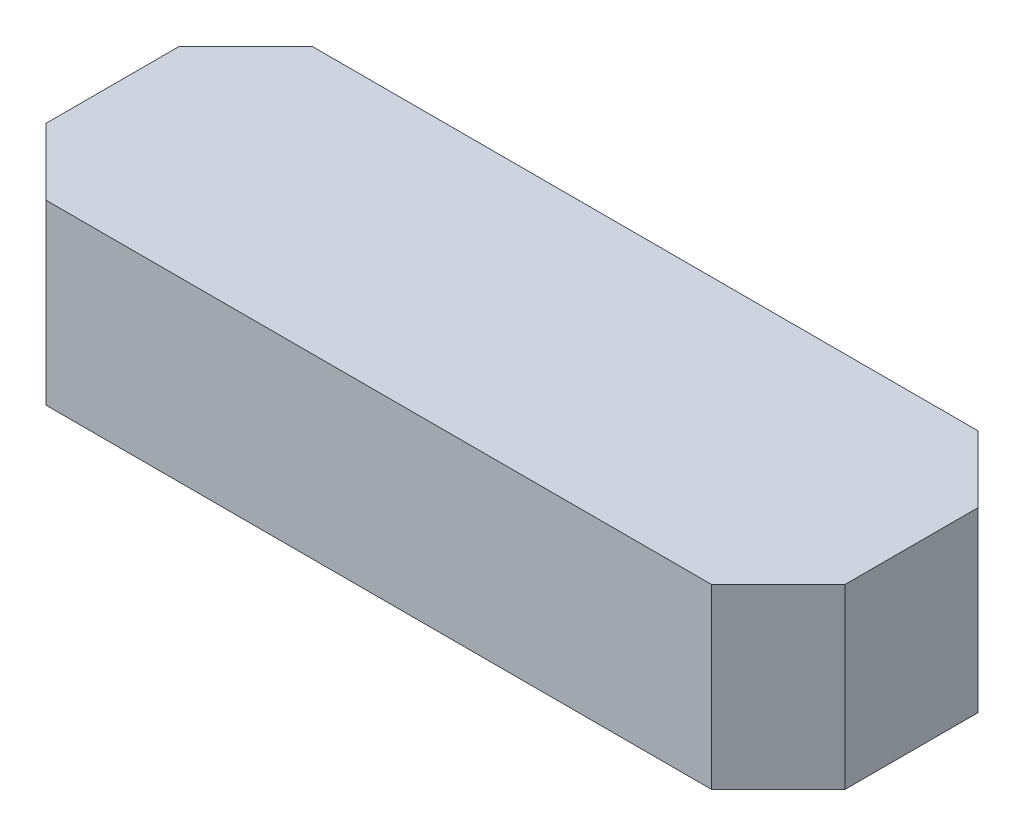
SolidWorks part; units mm, degrees
ref_plane "Front Plane" through (0, 0, 0) normal (0, 0, 1) x (1, 0, 0)
ref_plane "Top Plane" through (0, 0, 0) normal (0, 1, 0) x (1, 0, 0)
ref_plane "Right Plane" through (0, 0, 0) normal (1, 0, 0) x (0, 0, -1)
sketch "Sketch1" plane through (0, 0, 0) normal (0, 1, 0) x (1, 0, 0)
  line L4 (24.7236, 6.1432) -> (24.7236, 6.897)
  line L7 (-18, 6) -> (18, 6)
  line L8 (-18, 6) -> (-18, -6)
  line L9 (-18, -6) -> (18, -6)
  line L10 (18, 6) -> (18, -6)
  line L11 (-18, 6) -> (18, -6) construction
  line L12 (-18, -6) -> (18, 6) construction
  circle A0 centre (-11.845, 0) radius 4
  circle A1 centre (11.845, 0) radius 4
  point P0 (30.0754, 6.5201)
  point P5 (0, 0)
  dimension "D3" = 8
  dimension "D4" = 8
  dimension "D1" = 36
  dimension "D2" = 12
  dimension "D5" = 11.845
  dimension "D6" = 11.845
extrude "Boss-Extrude1" add sketch "Sketch1" against normal blind 5 contours L10 L7 L8 L9 A1 A0
sketch "Sketch2" plane through (0, 0, 0) normal (0, 1, 0) x (1, 0, 0)
  line L1 (-18, -6) -> (18, -6)
  line L2 (-18, -6) -> (-18, 6)
  line L3 (-18, 6) -> (18, 6)
  line L4 (18, -6) -> (18, 6)
  line L5 (-18, -6) -> (18, 6) construction
  line L6 (-18, 6) -> (18, -6) construction
  point P0 (0, 0)
extrude "Boss-Extrude2" add sketch "Sketch2" along normal blind 3
chamfer "Chamfer2" [suppressed] distance 3 angle 45
chamfer "Chamfer3" distance 3 angle 45 4 edges at (18, -1, 6) (18, -1, -6) (-18, -1, -6) (-18, -1, 6)
chamfer "Chamfer4" [suppressed] distance 2 distance2 6
